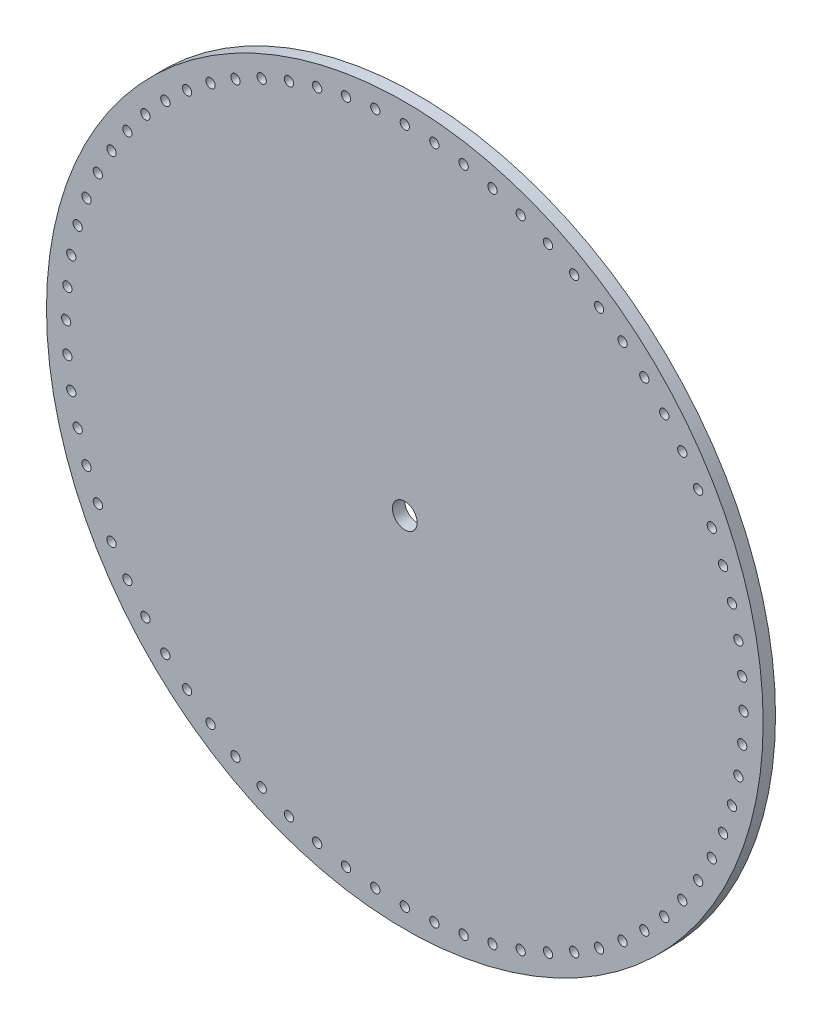
SolidWorks part; units mm, degrees
other "Markup1"
sketch "Sketch3"
ref_plane "Front Plane" through (0, 0, 0) normal (0, 0, 1) x (1, 0, 0)
ref_plane "Top Plane" through (0, 0, 0) normal (0, 1, 0) x (1, 0, 0)
ref_plane "Right Plane" through (0, 0, 0) normal (1, 0, 0) x (0, 0, -1)
sketch "Sketch2" plane through (0, 0, 0) normal (0, 0, 1) x (1, 0, 0)
  circle A0 centre (0, 0) radius 184.15
  dimension "D1" = 368.3
extrude "Boss-Extrude1" add sketch "Sketch2" along normal blind 6.35
sketch "Sketch8" plane through (0, 0, 6.35) normal (0, 0, 1) x (1, 0, 0)
  circle A0 centre (0, 0) radius 165.1
  dimension "D1" = 330.2
sketch "Sketch9" plane through (0, 0, 6.35) normal (0, 0, 1) x (1, 0, 0)
  circle A0 centre (-174.0492, 0) radius 2.3813
  dimension "D1" = 4.7625
extrude "Cut-Extrude4" cut sketch "Sketch9" against normal through all contours A0
pattern_circular "CirPattern1" count 72 over 360 about axis through (0, 0, 0) along (0, 0, 1) of "Cut-Extrude4"
sketch "Sketch10" plane through (0, 0, 0) normal (0, 0, -1) x (-1, 0, 0)
  circle A0 centre (0, 0) radius 17.4625
  circle A1 centre (0, 0) radius 6.35
  dimension "D1" = 34.925
  dimension "D2" = 12.7
extrude "Cut-Extrude7" cut sketch "Sketch10" against normal through all contours A1
